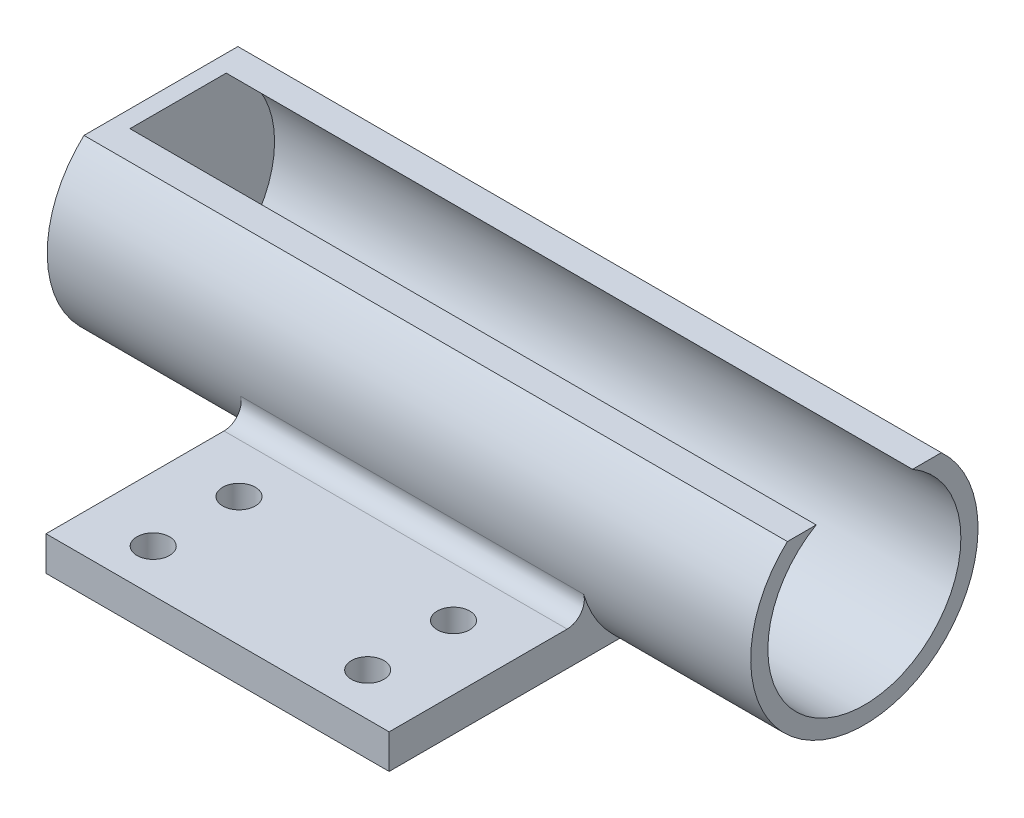
SolidWorks part; units mm, degrees
ref_plane "Front Plane" through (0, 0, 0) normal (0, 0, 1) x (1, 0, 0)
ref_plane "Top Plane" through (0, 0, 0) normal (0, 1, 0) x (1, 0, 0)
ref_plane "Right Plane" through (0, 0, 0) normal (1, 0, 0) x (0, 0, -1)
sketch "Sketch1" plane through (0, 0, 0) normal (0, 1, 0) x (1, 0, 0)
  line L0 (0, 10) -> (0, 0) construction
  line L1 (0, 5) -> (25, 5) construction
  line L2 (12.5, 5) -> (12.5, 15) construction
  line L3 (32.5, 15) -> (-7.5, 15)
  line L4 (32.5, 15) -> (32.5, -5)
  line L5 (32.5, -5) -> (-7.5, -5)
  line L6 (-7.5, 15) -> (-7.5, -5)
  line L7 (32.5, 15) -> (-7.5, -5) construction
  line L8 (32.5, -5) -> (-7.5, 15) construction
  circle A0 centre (0, 0) radius 1.9
  circle A1 centre (0, 10) radius 1.9
  circle A2 centre (25, 10) radius 1.9
  circle A3 centre (25, 0) radius 1.9
  point P7 (12.5, 5)
  dimension "D2" = 3.8
  dimension "D1" = 10
  dimension "D3" = 20
  dimension "D4" = 40
  dimension "D5" = 25
extrude "Boss-Extrude1" add sketch "Sketch1" along normal blind 4
sketch "Sketch3" plane through (32.5, 0, 0) normal (1, 0, 0) x (0, 0, -1)
  line L0 (24.7839, 20) -> (21.4242, 20)
  line L2 (15, 4) -> (18.7131, 4)
  line L3 (15, 0) -> (15, 4)
  line L4 (15, 0) -> (22, 0)
  line L5 (30.3964, -3) -> (5.2944, -3) construction
  line L6 (-5, 0) -> (15, 0) construction
  line L7 (-5, 4) -> (15, 4) construction
  line L8 (36.0089, 20) -> (39.3686, 20)
  line L9 (30.3964, -3) -> (30.3964, 23.9532) construction
  arc A0 (24.7839, 20) -> (36.0089, 20) centre (30.3964, 10.25) ccw
  arc A1 (21.4242, 20) -> (39.3686, 20) centre (30.3964, 10.25) ccw
  line M2 (15, 0) -> (15, 4)
  dimension "D2" = 22.5
  dimension "D1" = 2
  dimension "D3" = 7
  dimension "D4" = 3
  dimension "D5" = 16
extrude "Boss-Extrude2" add sketch "Sketch3" against normal up to surface (40 mm away) contours A1 L2 L4 M2 | L0 A1 L8 A0 up to face at (-7.5, 2, -5)
sketch "Sketch4" plane through (32.5, 0, 0) normal (1, 0, 0) x (0, 0, -1)
  line L0 (36.0089, 20) -> (39.3686, 20) construction
  line L1 (24.7839, 20) -> (21.4242, 20) construction
  line L2 (24.7839, 20) -> (21.4242, 20)
  line L3 (36.0089, 20) -> (39.3686, 20)
  arc A0 (24.7839, 20) -> (36.0089, 20) centre (30.3964, 10.25) ccw construction
  arc A1 (24.7839, 20) -> (36.0089, 20) centre (30.3964, 10.25) ccw
  arc A2 (21.4242, 20) -> (39.3686, 20) centre (30.3964, 10.25) ccw
extrude "Boss-Extrude3" add sketch "Sketch4" along normal blind 20
sketch "Sketch5" plane through (-7.5, 0, 0) normal (-1, 0, 0) x (0, 0, 1)
  line L2 (-21.4242, 20) -> (-24.7839, 20)
  line L3 (-36.0089, 20) -> (-39.3686, 20)
  line L4 (-21.4242, 20) -> (-24.7839, 20)
  line L5 (-36.0089, 20) -> (-39.3686, 20)
  arc A2 (-36.0089, 20) -> (-24.7839, 20) centre (-30.3964, 10.25) ccw
  arc A3 (-39.3686, 20) -> (-21.4242, 20) centre (-30.3964, 10.25) ccw
  arc A4 (-36.0089, 20) -> (-24.7839, 20) centre (-30.3964, 10.25) ccw
  arc A5 (-39.3686, 20) -> (-21.4242, 20) centre (-30.3964, 10.25) ccw
  dimension "D1" = 0
extrude "Boss-Extrude4" add sketch "Sketch5" along normal blind 20
fillet "Fillet1" radius 2 1 edges
ref_plane "Plane1" through (0, 0, -17.1464) normal (0, 0, 1) x (1, 0, 0)
ref_plane "Plane2" through (0, 0, -43.6464) normal (0, 0, -1) x (-1, 0, 0)
ref_plane "Plane3" through (12.5, 0, 0) normal (-1, 0, 0) x (0, 0, 1)
sketch "Sketch7" plane through (-27.5, 0, 0) normal (-1, 0, 0) x (0, 0, 1)
  line L0 (-39.3686, 20) -> (-21.4242, 20)
  arc A0 (-39.3686, 20) -> (-21.4242, 20) centre (-30.3964, 10.25) ccw
  arc A1 (-39.3686, 20) -> (-21.4242, 20) centre (-30.3964, 10.25) ccw construction
extrude "Boss-Extrude5" add sketch "Sketch7" along normal blind 2
